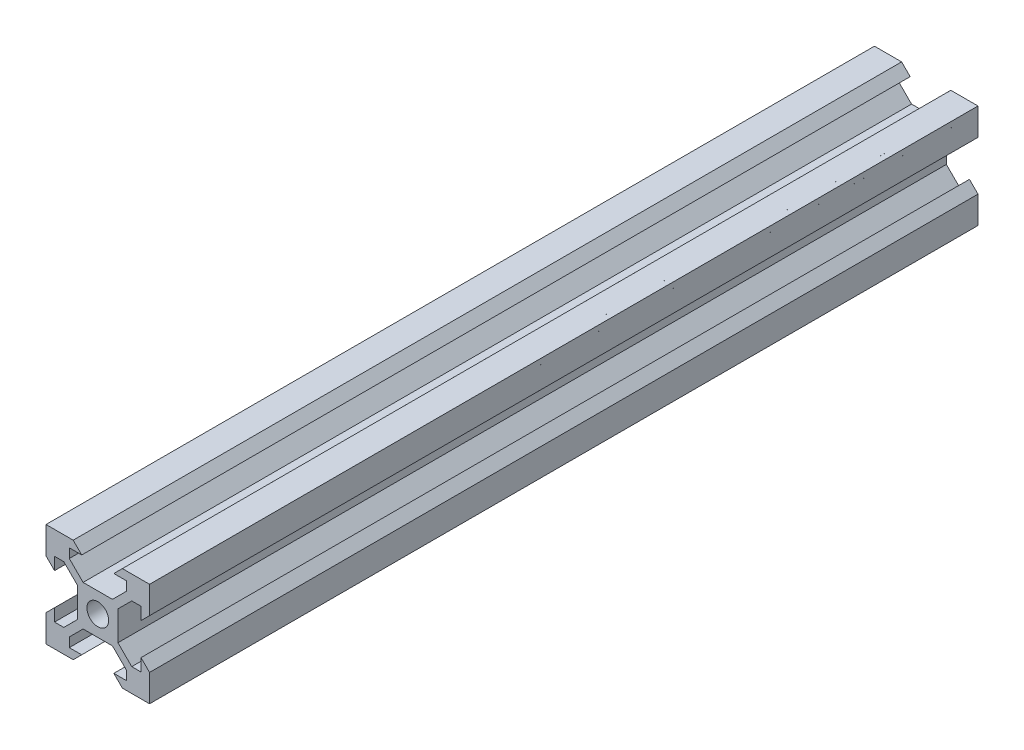
SolidWorks part; units mm, degrees
material "6061-T6 (SS)"
ref_plane "Front Plane" through (0, 0, 0) normal (0, 0, 1) x (1, 0, 0)
ref_plane "Top Plane" through (0, 0, 0) normal (0, 1, 0) x (1, 0, 0)
ref_plane "Right Plane" through (0, 0, 0) normal (1, 0, 0) x (0, 0, -1)
sketch "Sketch1" plane through (0, 0, 0) normal (0, 0, 1) x (1, 0, 0)
  line L0 (2.8343, 3.894) -> (5.5, 6.5588)
  line L1 (2.8343, -3.894) -> (-2.8343, -3.894)
  line L2 (3.8948, -2.8332) -> (3.8948, 2.8332)
  line L3 (2.8343, 3.894) -> (-2.8343, 3.894)
  line L4 (-3.8948, -2.8332) -> (-3.8948, 2.8332)
  line L5 (3.8994, -3.9006) -> (-3.8994, 3.9006) construction
  line L6 (3.9006, 3.8994) -> (-3.9006, -3.8994) construction
  line L7 (10, 4.747) -> (10, 9.9986)
  line L8 (5.5, 6.5588) -> (5.5, 8.3491)
  line L9 (5.5, 8.3491) -> (3.1, 8.3491)
  line L10 (3.1, 8.3491) -> (4.75, 9.9986)
  line L11 (4.75, 9.9986) -> (10, 9.9986)
  line L12 (8.35, 3.0975) -> (10, 4.747)
  line L13 (8.3507, 5.4975) -> (8.35, 3.0975)
  line L14 (6.5605, 5.498) -> (8.3507, 5.4975)
  line L15 (3.8948, 2.8332) -> (6.5605, 5.498)
  line L16 (0, -55) -> (0, 55) construction
  line L17 (-3.8948, 2.8332) -> (-6.5605, 5.498)
  line L18 (-6.5605, 5.498) -> (-8.3507, 5.4975)
  line L19 (-8.3507, 5.4975) -> (-8.35, 3.0975)
  line L20 (-8.35, 3.0975) -> (-10, 4.747)
  line L21 (-4.75, 9.9986) -> (-10, 9.9986)
  line L22 (-3.1, 8.3491) -> (-4.75, 9.9986)
  line L23 (-5.5, 8.3491) -> (-3.1, 8.3491)
  line L24 (-5.5, 6.5588) -> (-5.5, 8.3491)
  line L25 (-10, 4.747) -> (-10, 9.9986)
  line L26 (-2.8343, 3.894) -> (-5.5, 6.5588)
  line L27 (55, 0) -> (-55, 0) construction
  line L28 (3.8948, -2.8332) -> (6.5605, -5.498)
  line L29 (2.8343, -3.894) -> (5.5, -6.5588)
  line L30 (-3.8948, -2.8332) -> (-6.5605, -5.498)
  line L31 (-2.8343, -3.894) -> (-5.5, -6.5588)
  line L32 (-8.3507, -5.4975) -> (-8.35, -3.0975)
  line L33 (-8.35, -3.0975) -> (-10, -4.747)
  line L34 (8.3507, -5.4975) -> (8.35, -3.0975)
  line L35 (8.35, -3.0975) -> (10, -4.747)
  line L36 (-10, -4.747) -> (-10, -9.9986)
  line L37 (-5.5, -6.5588) -> (-5.5, -8.3491)
  line L38 (-5.5, -8.3491) -> (-3.1, -8.3491)
  line L39 (-3.1, -8.3491) -> (-4.75, -9.9986)
  line L40 (-4.75, -9.9986) -> (-10, -9.9986)
  line L41 (-6.5605, -5.498) -> (-8.3507, -5.4975)
  line L42 (6.5605, -5.498) -> (8.3507, -5.4975)
  line L43 (4.75, -9.9986) -> (10, -9.9986)
  line L44 (3.1, -8.3491) -> (4.75, -9.9986)
  line L45 (5.5, -8.3491) -> (3.1, -8.3491)
  line L46 (5.5, -6.5588) -> (5.5, -8.3491)
  line L47 (10, -4.747) -> (10, -9.9986)
  circle A0 centre (0, 0) radius 2.1
  point P0 (0, 0)
  dimension "D6" = 4.2
  dimension "D1" = 7.8
  dimension "D2" = 20
  dimension "D3" = 11
  dimension "D4" = 9.5
  dimension "D5" = 6.2
  dimension "D7" = 1.5
extrude "Boss-Extrude1" add sketch "Sketch1" along normal mid plane 160
